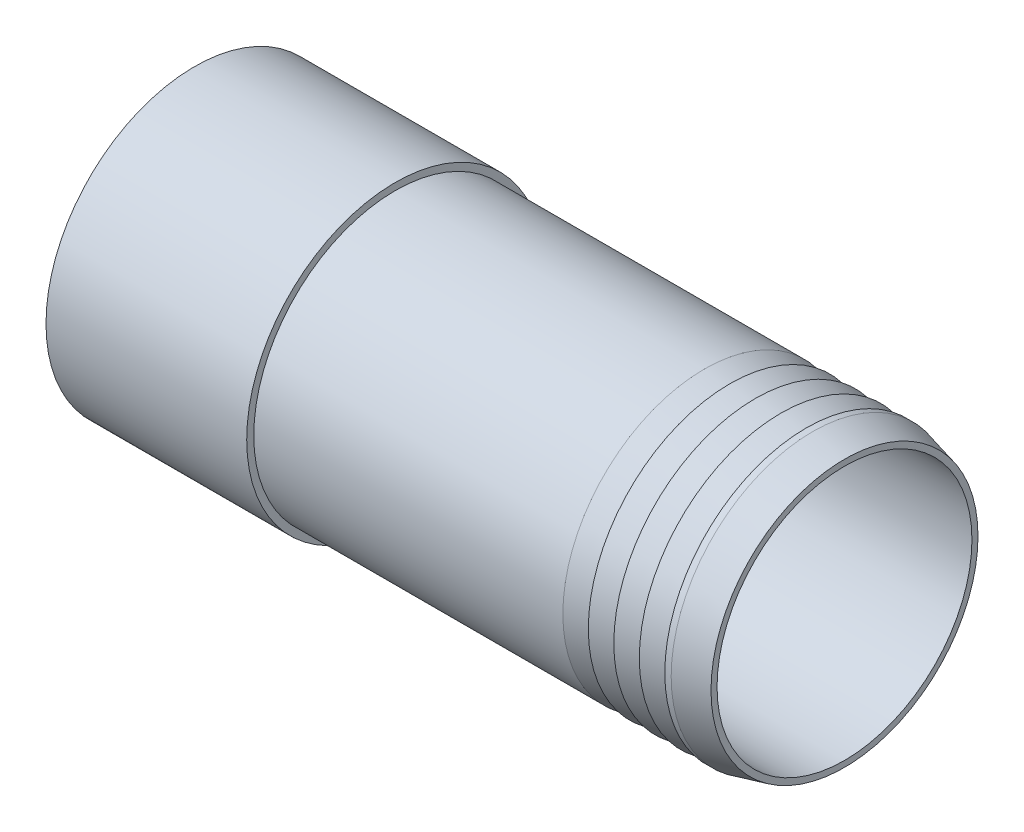
SolidWorks part; units mm, degrees
ref_plane "Plan de face" through (0, 0, 0) normal (0, 0, 1) x (1, 0, 0)
ref_plane "Plan de dessus" through (0, 0, 0) normal (0, 1, 0) x (1, 0, 0)
ref_plane "Plan de droite" through (0, 0, 0) normal (1, 0, 0) x (0, 0, -1)
ref_plane "Plan1"
sketch "Esquisse1" plane through (0, 0, 0) normal (0, 0, 1) x (1, 0, 0)
  line L0 (-45.72, 5.08) -> (19.05, 5.08)
  line L1 (19.05, 5.08) -> (19.05, 6.477)
  line L2 (19.05, 6.477) -> (15.24, 6.477)
  line L3 (15.24, 6.477) -> (15.24, 5.842)
  line L4 (15.24, 5.842) -> (12.7, 6.477)
  line L5 (12.7, 6.477) -> (12.7, 5.842)
  line L6 (12.7, 5.842) -> (10.16, 6.477)
  line L7 (10.16, 6.477) -> (10.16, 5.842)
  line L8 (10.16, 5.842) -> (7.62, 6.477)
  line L9 (7.62, 6.477) -> (7.62, 5.842)
  line L10 (7.62, 5.842) -> (5.08, 6.477)
  line L11 (5.08, 6.477) -> (-25.72, 6.477)
  line L12 (-25.72, 6.477) -> (-25.72, 7.18)
  line L13 (-25.72, 7.18) -> (-45.72, 7.18)
  line L14 (-45.72, 7.18) -> (-45.72, 5.08)
  line L15 (0, -7.62) -> (142.9139, -7.62) construction
revolve "Revolution1" add sketch "Esquisse1" angle 360 about L15
chamfer "Chamfer1" distance 0.7938 distance2 3.175 1 edges at (19.05, -7.62, 14.097)
ref_plane "Plan2"
